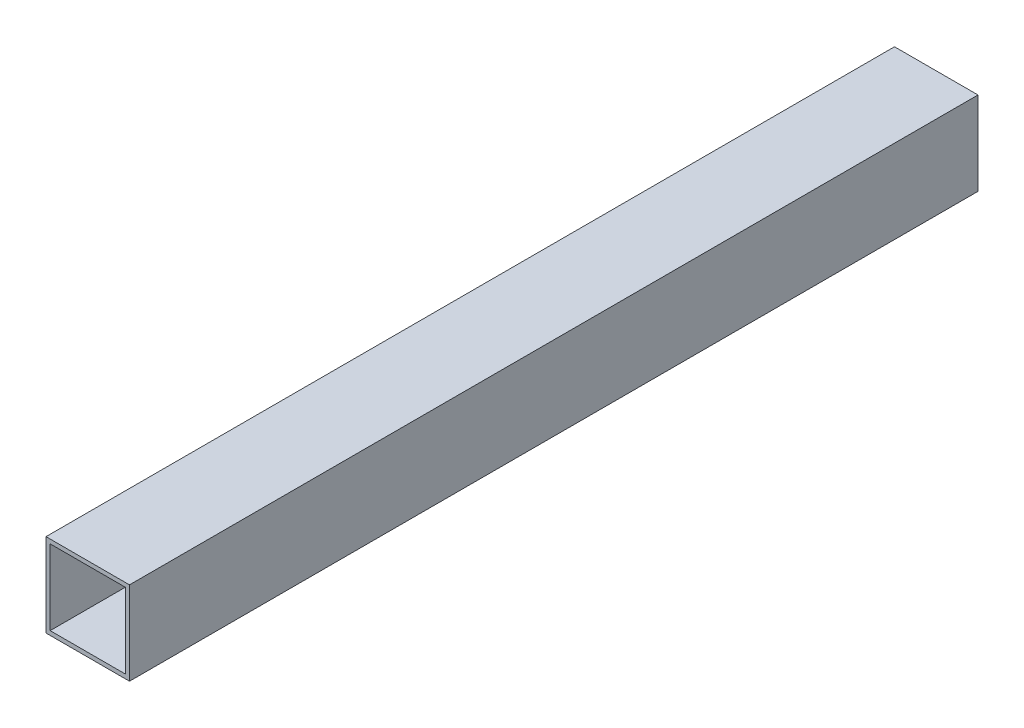
SolidWorks part; units mm, degrees
ref_plane "Alzado" through (0, 0, 0) normal (0, 0, 1) x (1, 0, 0)
ref_plane "Planta" through (0, 0, 0) normal (0, 1, 0) x (1, 0, 0)
ref_plane "Vista lateral" through (0, 0, 0) normal (1, 0, 0) x (0, 0, -1)
sketch "Croquis1" plane through (0, 0, 0) normal (0, 0, 1) x (1, 0, 0)
  line L1 (20, -20) -> (-20, -20)
  line L2 (20, -20) -> (20, 20)
  line L3 (20, 20) -> (-20, 20)
  line L4 (-20, -20) -> (-20, 20)
  line L5 (20, -20) -> (-20, 20) construction
  line L6 (20, 20) -> (-20, -20) construction
  point P0 (0, 0)
  dimension "D1" = 40
  dimension "D2" = 40
extrude "Extruir-Lámina1" add sketch "Croquis1" along normal blind 406.5 thin
sketch "Croquis2" plane through (20, 0, 0) normal (1, 0, 0) x (0, 0, -1)
  circle A1 centre (-148.2375, -1.1424) radius 5
  circle A2 centre (-148.2375, -1.1424) radius 5
  circle A3 centre (-258.2375, -1.1424) radius 5
  circle A4 centre (-258.2375, -1.1424) radius 5
  dimension "D1" = 0
  dimension "D2" = 0
